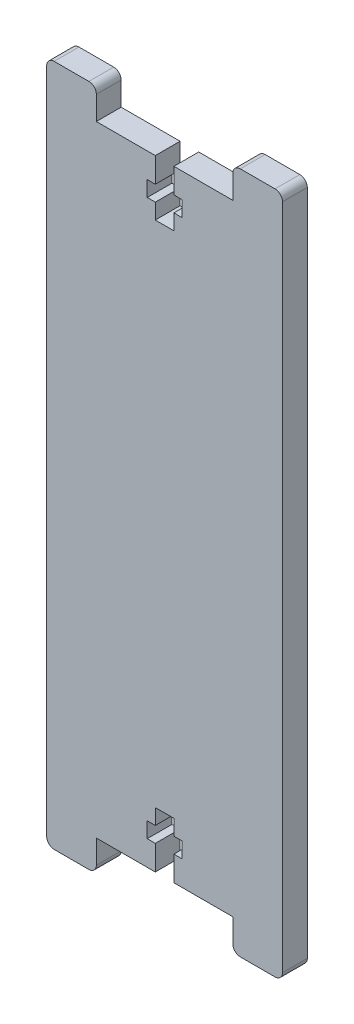
SolidWorks part; units mm, degrees
ref_plane "前视基准面" through (0, 0, 0) normal (0, 0, 1) x (1, 0, 0)
ref_plane "上视基准面" through (0, 0, 0) normal (0, 1, 0) x (1, 0, 0)
ref_plane "右视基准面" through (0, 0, 0) normal (1, 0, 0) x (0, 0, -1)
sketch "草图1" plane through (0, 0, 0) normal (0, 0, 1) x (1, 0, 0)
  line L0 (-4.0909, 0) -> (-4.0909, 7.8) construction
  line L1 (14.9091, 14) -> (14.9091, -96)
  line L2 (14.9091, -41) -> (-23.0909, -41) construction
  line L3 (-4.0909, -82) -> (-4.0909, -89.8) construction
  line L4 (6.9091, -96) -> (14.9091, -96)
  line L5 (6.9091, -91) -> (6.9091, -96)
  line L6 (-5.5909, 0) -> (-2.5909, 0)
  line L7 (-2.5909, 0) -> (-2.5909, 2.5)
  line L8 (-2.5909, 2.5) -> (-1.2909, 2.5)
  line L9 (-1.2909, 2.5) -> (-1.2909, 5)
  line L10 (-1.2909, 5) -> (-2.5909, 5)
  line L11 (-2.5909, 5) -> (-2.5909, 9)
  line L12 (-2.5909, 9) -> (6.9091, 9)
  line L13 (6.9091, 9) -> (6.9091, 14)
  line L14 (6.9091, 14) -> (14.9091, 14)
  line L15 (-2.5909, -91) -> (6.9091, -91)
  line L16 (-2.5909, -87) -> (-2.5909, -91)
  line L17 (-1.2909, -87) -> (-2.5909, -87)
  line L18 (-1.2909, -84.5) -> (-1.2909, -87)
  line L19 (-2.5909, -84.5) -> (-1.2909, -84.5)
  line L20 (-2.5909, -82) -> (-2.5909, -84.5)
  line L21 (-5.5909, -82) -> (-2.5909, -82)
  line L22 (-5.5909, -82) -> (-5.5909, -84.5)
  line L23 (-5.5909, -84.5) -> (-6.8909, -84.5)
  line L24 (-6.8909, -84.5) -> (-6.8909, -87)
  line L25 (-6.8909, -87) -> (-5.5909, -87)
  line L26 (-5.5909, -87) -> (-5.5909, -91)
  line L27 (-5.5909, -91) -> (-15.0909, -91)
  line L28 (-15.0909, 14) -> (-23.0909, 14)
  line L29 (-15.0909, 9) -> (-15.0909, 14)
  line L30 (-5.5909, 9) -> (-15.0909, 9)
  line L31 (-5.5909, 5) -> (-5.5909, 9)
  line L32 (-6.8909, 5) -> (-5.5909, 5)
  line L33 (-6.8909, 2.5) -> (-6.8909, 5)
  line L34 (-5.5909, 2.5) -> (-6.8909, 2.5)
  line L35 (-5.5909, 0) -> (-5.5909, 2.5)
  line L36 (-15.0909, -91) -> (-15.0909, -96)
  line L37 (-15.0909, -96) -> (-23.0909, -96)
  line L38 (-23.0909, 14) -> (-23.0909, -96)
  point P26 (-4.0909, -41)
  dimension "D1" = 1.5
  dimension "D2" = 2.5
  dimension "D3" = 2.8
  dimension "D4" = 2.5
  dimension "D5" = 4
  dimension "D6" = 9.5
  dimension "D7" = 5
  dimension "D8" = 8
  dimension "D9" = 110
extrude "凸台-拉伸1" add sketch "草图1" along normal blind 4
sketch "草图2" plane through (0, -91, 0) normal (0, -1, 0) x (1, 0, 0)
  line L0 (-5.5909, 2) -> (-2.5909, 2)
  line L1 (-5.5909, 4) -> (-5.5909, 0) construction
  line L2 (-2.5909, 4) -> (-2.5909, 0) construction
  circle A0 centre (-4.0909, 2) radius 1.5
fillet "圆角1" radius 1.2 8 edges at (-23.0909, 14, 2) (-15.0909, 14, 2) (6.9091, 14, 2) (14.9091, 14, 2) (-23.0909, -96, 2) (-15.0909, -96, 2) (6.9091, -96, 2) (14.9091, -96, 2)
